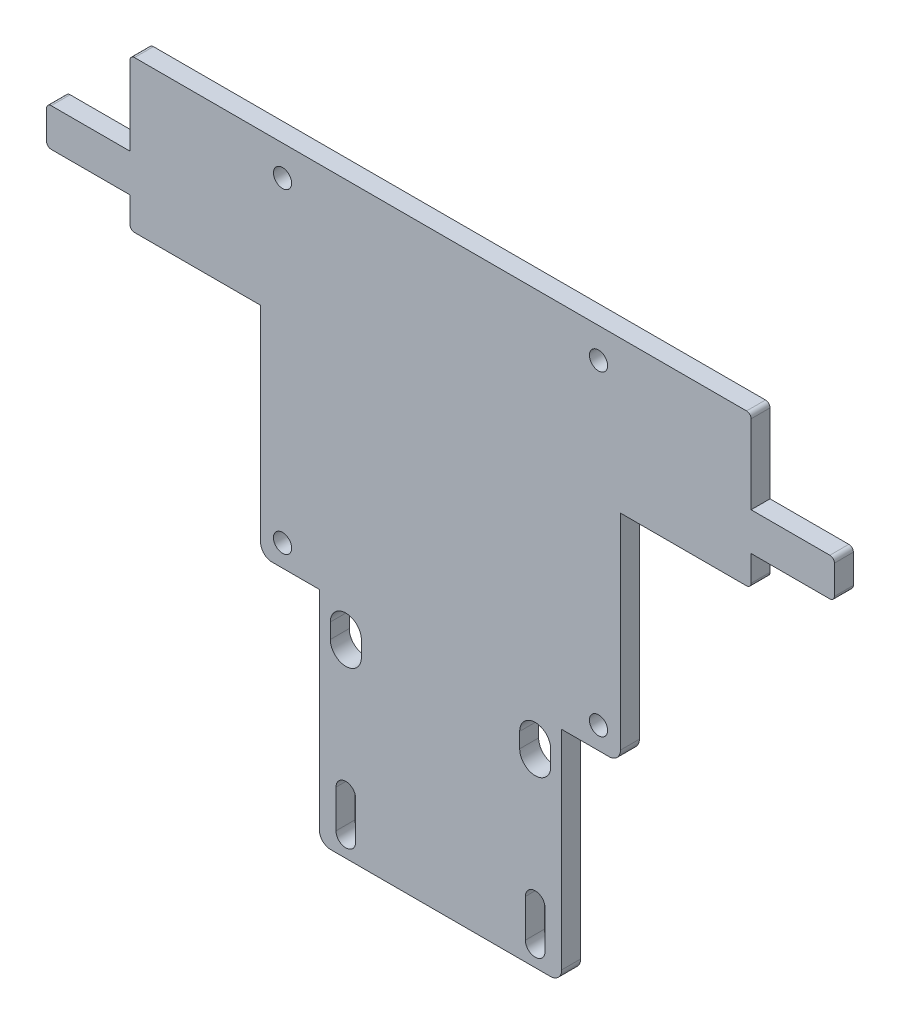
SolidWorks part; units mm, degrees
ref_plane "Front Plane" through (0, 0, 0) normal (0, 0, 1) x (1, 0, 0)
ref_plane "Top Plane" through (0, 0, 0) normal (0, 1, 0) x (1, 0, 0)
ref_plane "Right Plane" through (0, 0, 0) normal (1, 0, 0) x (0, 0, -1)
sketch "Sketch1" plane through (0, 0, 0) normal (0, 0, 1) x (1, 0, 0)
  line L0 (52.07, 25.4) -> (52.07, -6.1659) construction
  line L1 (0.762, 0) -> (21.9075, 0)
  line L2 (0, 0.762) -> (0, 5.08)
  line L3 (0.762, 25.4) -> (103.378, 25.4)
  line L4 (104.14, 0.762) -> (104.14, 5.08)
  line L5 (-13.208, 5.08) -> (0, 5.08)
  line L6 (-13.97, 5.842) -> (-13.97, 10.668)
  line L7 (-13.208, 11.43) -> (0, 11.43)
  line L8 (118.11, 5.842) -> (118.11, 10.668)
  line L9 (-13.97, 8.255) -> (118.11, 8.255) construction
  line L10 (0, 11.43) -> (0, 24.638)
  line L11 (104.14, 11.43) -> (117.348, 11.43)
  line L12 (104.14, 11.43) -> (104.14, 24.638)
  line L13 (104.14, 5.08) -> (117.348, 5.08)
  line L14 (21.9075, -6.1659) -> (82.2325, -6.1659) construction
  line L15 (36.195, -41.4084) -> (67.945, -41.4084) construction
  line L16 (23.8125, -36.3284) -> (31.75, -36.3284)
  line L17 (21.9075, -34.4233) -> (21.9075, 0)
  line L19 (82.2325, -34.4233) -> (82.2325, 0)
  line L20 (36.195, -40.1384) -> (36.195, -42.6784) construction
  line L21 (72.39, -36.3284) -> (80.3275, -36.3284)
  line L23 (31.75, -36.3284) -> (31.75, -71.2534)
  line L24 (33.655, -73.1584) -> (70.485, -73.1584)
  line L25 (72.39, -36.3284) -> (72.39, -71.2534)
  line L26 (38.7985, -40.1384) -> (38.7985, -42.6784)
  line L27 (33.5915, -40.1384) -> (33.5915, -42.6784)
  line L28 (67.945, -40.1384) -> (67.945, -42.6784) construction
  line L29 (82.2325, 0) -> (103.378, 0)
  line L30 (70.5485, -40.1384) -> (70.5485, -42.6784)
  line L31 (65.3415, -40.1384) -> (65.3415, -42.6784)
  line L32 (36.195, -66.8084) -> (67.945, -66.8084) construction
  line L33 (67.945, -63.6334) -> (67.945, -69.9834) construction
  line L34 (69.595, -63.6334) -> (69.595, -69.9834)
  line L35 (66.295, -63.6334) -> (66.295, -69.9834)
  line L36 (36.195, -63.6334) -> (36.195, -69.9834) construction
  line L37 (37.845, -63.6334) -> (37.845, -69.9834)
  line L38 (34.545, -63.6334) -> (34.545, -69.9834)
  arc A0 (103.378, 0) -> (104.14, 0.762) centre (103.378, 0.762) ccw
  arc A1 (0.762, 0) -> (0, 0.762) centre (0.762, 0.762) cw
  arc A2 (-13.208, 5.08) -> (-13.97, 5.842) centre (-13.208, 5.842) cw
  arc A3 (-13.97, 10.668) -> (-13.208, 11.43) centre (-13.208, 10.668) cw
  arc A4 (117.348, 5.08) -> (118.11, 5.842) centre (117.348, 5.842) ccw
  arc A5 (117.348, 11.43) -> (118.11, 10.668) centre (117.348, 10.668) cw
  arc A6 (103.378, 25.4) -> (104.14, 24.638) centre (103.378, 24.638) cw
  arc A7 (0, 24.638) -> (0.762, 25.4) centre (0.762, 24.638) cw
  circle A9 centre (25.5841, 20.32) radius 1.524
  circle A10 centre (78.5558, 20.32) radius 1.524
  circle A11 centre (78.5558, -32.6517) radius 1.524
  circle A12 centre (25.5841, -32.6517) radius 1.524
  arc A13 (80.3275, -36.3284) -> (82.2325, -34.4233) centre (80.3275, -34.4234) ccw
  arc A14 (23.8125, -36.3284) -> (21.9075, -34.4233) centre (23.8125, -34.4234) cw
  arc A15 (70.485, -73.1584) -> (72.39, -71.2534) centre (70.485, -71.2534) ccw
  arc A16 (31.75, -71.2534) -> (33.655, -73.1584) centre (33.655, -71.2534) ccw
  arc A17 (38.7985, -40.1384) -> (33.5915, -40.1384) centre (36.195, -40.1384) ccw
  arc A18 (33.5915, -42.6784) -> (38.7985, -42.6784) centre (36.195, -42.6784) ccw
  arc A19 (70.5485, -40.1384) -> (65.3415, -40.1384) centre (67.945, -40.1384) ccw
  arc A20 (65.3415, -42.6784) -> (70.5485, -42.6784) centre (67.945, -42.6784) ccw
  arc A21 (69.595, -63.6334) -> (66.295, -63.6334) centre (67.945, -63.6334) ccw
  arc A22 (66.295, -69.9834) -> (69.595, -69.9834) centre (67.945, -69.9834) ccw
  arc A23 (37.845, -63.6334) -> (34.545, -63.6334) centre (36.195, -63.6334) ccw
  arc A24 (34.545, -69.9834) -> (37.845, -69.9834) centre (36.195, -69.9834) ccw
  point P21 (0, 0)
  point P24 (-13.97, 5.08)
  point P27 (-13.97, 11.43)
  point P34 (104.14, 25.4)
  point P37 (0, 25.4)
  point P50 (52.07, -73.1584)
  point P59 (52.07, -41.4084)
  point P64 (36.195, -41.4084)
  point P76 (67.945, -41.4084)
  point P85 (52.07, -66.8084)
  point P87 (67.945, -66.8084)
  point P93 (36.195, -66.8084)
  point P99 (52.07, -67.0549)
  point P100 (52.07, -67.1141)
  point P101 (52.07, -67.2889)
  point P102 (52.07, -67.108)
  point P103 (37.845, -64.137)
  dimension "D6" = 0.762
  dimension "D7" = 40.64
  dimension "D8" = 52.9717
  dimension "D10" = 3.048
  dimension "D13" = 1.905
  dimension "D18" = 1.905
  dimension "D19" = 2.6035
  dimension "D21" = 1.65
  dimension "D1" = 25.4
  dimension "D2" = 104.14
  dimension "D3" = 6.35
  dimension "D4" = 132.08
  dimension "D5" = 17.145
  dimension "D9" = 5.08
  dimension "D11" = 26.4859
  dimension "D12" = 31.75
  dimension "D14" = 5.08
  dimension "D15" = 31.75
  dimension "D16" = 60.325
  dimension "D17" = 30.1625
  dimension "D20" = 2.54
  dimension "D22" = 6.35
  dimension "D23" = 31.75
  dimension "D24" = 6.35
extrude "Boss-Extrude1" add sketch "Sketch1" along normal blind 3.175
